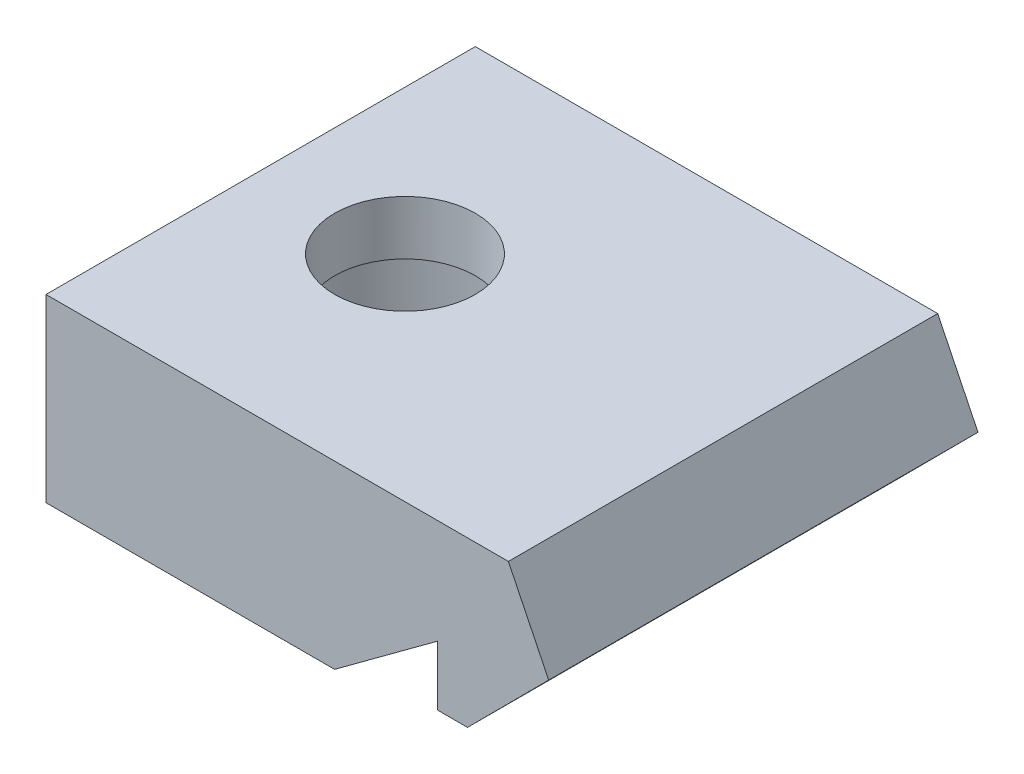
SolidWorks part; units mm, degrees
ref_plane "정면" through (0, 0, 0) normal (0, 0, 1) x (1, 0, 0)
ref_plane "윗면" through (0, 0, 0) normal (0, 1, 0) x (1, 0, 0)
ref_plane "우측면" through (0, 0, 0) normal (1, 0, 0) x (0, 0, -1)
sketch "스케치1" plane through (0, 0, 0) normal (0, 0, 1) x (1, 0, 0)
  line L0 (8, -5) -> (10.8493, -2.899)
  line L1 (0, 0) -> (8, 0)
  line L2 (0, 0) -> (0, -5)
  line L3 (0, -5) -> (8, -5)
  line L4 (8, 0) -> (8, -5)
  line L5 (10.8493, -2.899) -> (10.8493, -4.5512)
  line L7 (13.9338, -2.2909) -> (12.8168, 0)
  line L8 (12.8168, 0) -> (8, 0)
  line L9 (10.8493, -4.5512) -> (11.6837, -4.5512)
  line L10 (11.6837, -4.5512) -> (13.9338, -2.2909)
  dimension "D1" = 8
  dimension "D2" = 5
extrude "보스-돌출1" add sketch "스케치1" along normal mid plane 11.9
sketch "스케치2" plane through (0, -5, 0) normal (0, -1, 0) x (1, 0, 0)
  line L0 (0, 0) -> (4, 0) construction
  line L1 (0, 5.95) -> (0, -5.95) construction
  circle A0 centre (4, 0) radius 1.95
  dimension "D1" = 3.9
  dimension "D2" = 4
extrude "컷-돌출1" cut sketch "스케치2" against normal up to next
sketch "스케치3" plane through (0, -5, 0) normal (0, -1, 0) x (1, 0, 0)
  circle A0 centre (4, 0) radius 3.5
  dimension "D1" = 7
extrude "컷-돌출2" cut sketch "스케치3" against normal blind 3.5 contours A0
